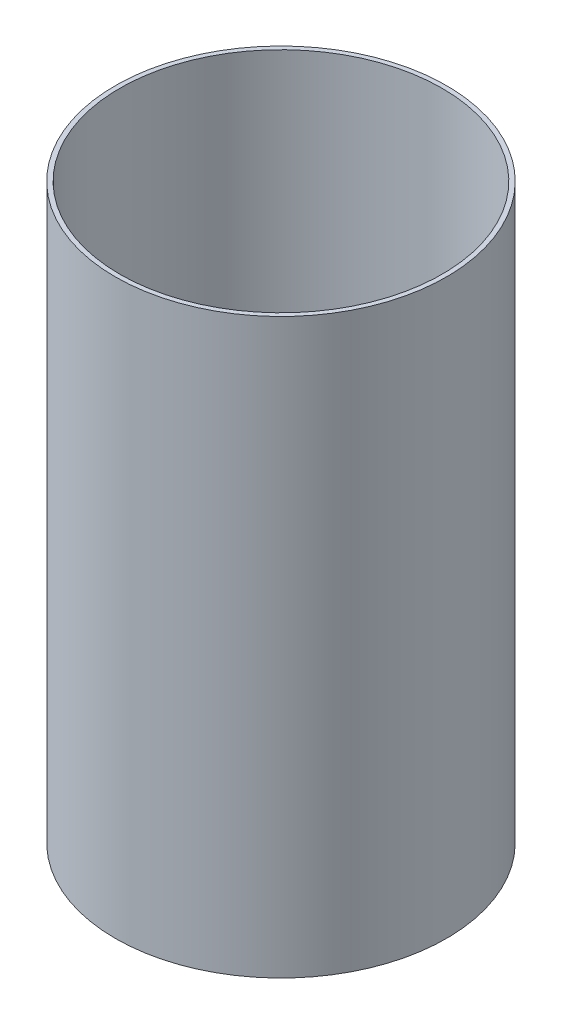
SolidWorks part; units mm, degrees
ref_plane "Front Plane" through (0, 0, 0) normal (0, 0, 1) x (1, 0, 0)
ref_plane "Top Plane" through (0, 0, 0) normal (0, 1, 0) x (1, 0, 0)
ref_plane "Right Plane" through (0, 0, 0) normal (1, 0, 0) x (0, 0, -1)
sketch "Sketch1" plane through (0, 0, 0) normal (0, 1, 0) x (1, 0, 0)
  circle A0 centre (0, 0) radius 14.2875
  circle A1 centre (0, 0) radius 14.6875
  dimension "D1" = 28.575
  dimension "D2" = 0.4
extrude "Boss-Extrude1" add sketch "Sketch1" along normal mid plane 50.8
